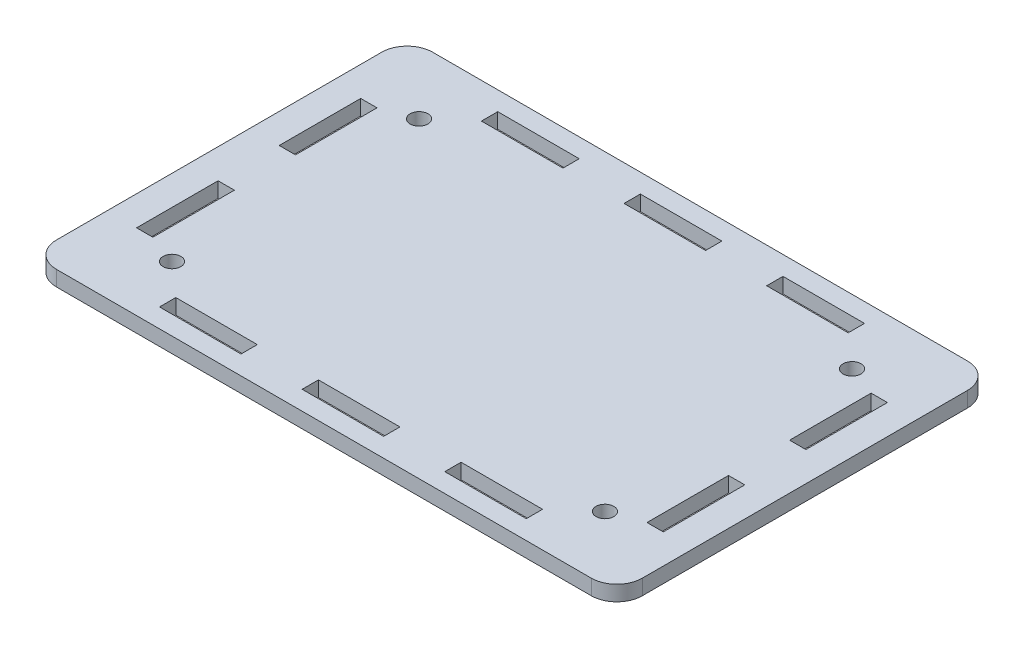
SolidWorks part; units mm, degrees
ref_plane "Front Plane" through (0, 0, 0) normal (0, 0, 1) x (1, 0, 0)
ref_plane "Top Plane" through (0, 0, 0) normal (0, 1, 0) x (1, 0, 0)
ref_plane "Right Plane" through (0, 0, 0) normal (1, 0, 0) x (0, 0, -1)
sketch "Sketch1" plane through (0, 0, 0) normal (0, 1, 0) x (1, 0, 0)
  line L0 (-20, 30) -> (-8, 30) construction
  line L1 (-57.5, -36.9246) -> (57.5, -36.9246)
  line L2 (-57.5, -36.9246) -> (-57.5, 36.9246)
  line L3 (-57.5, 36.9246) -> (57.5, 36.9246)
  line L4 (57.5, -36.9246) -> (57.5, 36.9246)
  line L5 (-57.5, -36.9246) -> (57.5, 36.9246) construction
  line L6 (-57.5, 36.9246) -> (57.5, -36.9246) construction
  line L7 (-51.7, -33.2) -> (51.7, -33.2) construction
  line L8 (-51.7, -33.2) -> (-51.7, 33.2) construction
  line L9 (-51.7, 33.2) -> (51.7, 33.2) construction
  line L10 (51.7, -33.2) -> (51.7, 33.2) construction
  line L11 (-51.7, -33.2) -> (51.7, 33.2) construction
  line L12 (-51.7, 33.2) -> (51.7, -33.2) construction
  line L13 (-36, 33.2) -> (-20, 33.2)
  line L14 (-36, 33.2) -> (-36, 30)
  line L15 (-36, 30) -> (-20, 30)
  line L16 (-20, 33.2) -> (-20, 30)
  line L17 (20, 33.2) -> (36, 33.2)
  line L18 (20, 33.2) -> (20, 30)
  line L19 (20, 30) -> (36, 30)
  line L20 (36, 33.2) -> (36, 30)
  line L29 (-51.7, 22) -> (-48.5, 22)
  line L30 (-51.7, 22) -> (-51.7, 6)
  line L31 (-51.7, 6) -> (-48.5, 6)
  line L32 (-48.5, 22) -> (-48.5, 6)
  line L33 (-51.7, -6) -> (-48.5, -6)
  line L34 (-51.7, -6) -> (-51.7, -22)
  line L35 (-51.7, -22) -> (-48.5, -22)
  line L36 (-48.5, -6) -> (-48.5, -22)
  line L49 (-8, 33.2) -> (8, 33.2)
  line L50 (-8, 33.2) -> (-8, 30)
  line L51 (-8, 30) -> (8, 30)
  line L52 (8, 33.2) -> (8, 30)
  line L53 (8, 30) -> (20, 30) construction
  line L54 (-48.5, 6) -> (-48.5, -6) construction
  line L55 (-42.5, 24.25) -> (-42.5, -24.25) construction
  line L56 (-42.5, -24.25) -> (42.5, -24.25) construction
  line L57 (0, 0) -> (0, 30) construction
  line L58 (51.7, 0) -> (0, 0) construction
  line L59 (-36, -30) -> (-20, -30)
  line L60 (-20, -33.2) -> (-20, -30)
  line L61 (-36, -33.2) -> (-20, -33.2)
  line L62 (-36, -33.2) -> (-36, -30)
  line L63 (20, -30) -> (36, -30)
  line L64 (36, -33.2) -> (36, -30)
  line L65 (20, -33.2) -> (36, -33.2)
  line L66 (20, -33.2) -> (20, -30)
  line L67 (-8, -30) -> (8, -30)
  line L68 (8, -33.2) -> (8, -30)
  line L69 (-8, -33.2) -> (8, -33.2)
  line L70 (-8, -33.2) -> (-8, -30)
  line L71 (51.7, -22) -> (48.5, -22)
  line L72 (48.5, -6) -> (48.5, -22)
  line L73 (51.7, -6) -> (48.5, -6)
  line L74 (51.7, -6) -> (51.7, -22)
  line L75 (51.7, 6) -> (48.5, 6)
  line L76 (48.5, 22) -> (48.5, 6)
  line L77 (51.7, 22) -> (48.5, 22)
  line L78 (51.7, 22) -> (51.7, 6)
  circle A0 centre (-42.5, 24.25) radius 1.75
  circle A1 centre (42.5, 24.25) radius 1.75
  circle A2 centre (-42.5, -24.25) radius 1.75
  circle A3 centre (42.5, -24.25) radius 1.75
  point P0 (0, 0)
  point P5 (0, 0)
  point P19 (-42.5, 0)
  point P20 (0, 30)
  point P21 (0, 33.2)
  point P23 (-48.5, 0)
  point P24 (-51.7, 0)
  point P73 (0, -24.25)
  point P74 (0, -36.9246)
  point P75 (-57.5, 0)
  dimension "D6" = 3.5
  dimension "D2" = 115
  dimension "D3" = 60
  dimension "D4" = 85
  dimension "D5" = 48.5
  dimension "D7" = 3.2
  dimension "D8" = 16
  dimension "D9" = 12
  dimension "D10" = 12
  dimension "D11" = 97
extrude "Boss-Extrude1" add sketch "Sketch1" along normal blind 3
fillet "Fillet1" radius 5 4 edges at (-57.5, 1.5, -36.9246) (57.5, 1.5, -36.9246) (57.5, 1.5, 36.9246) (-57.5, 1.5, 36.9246)
